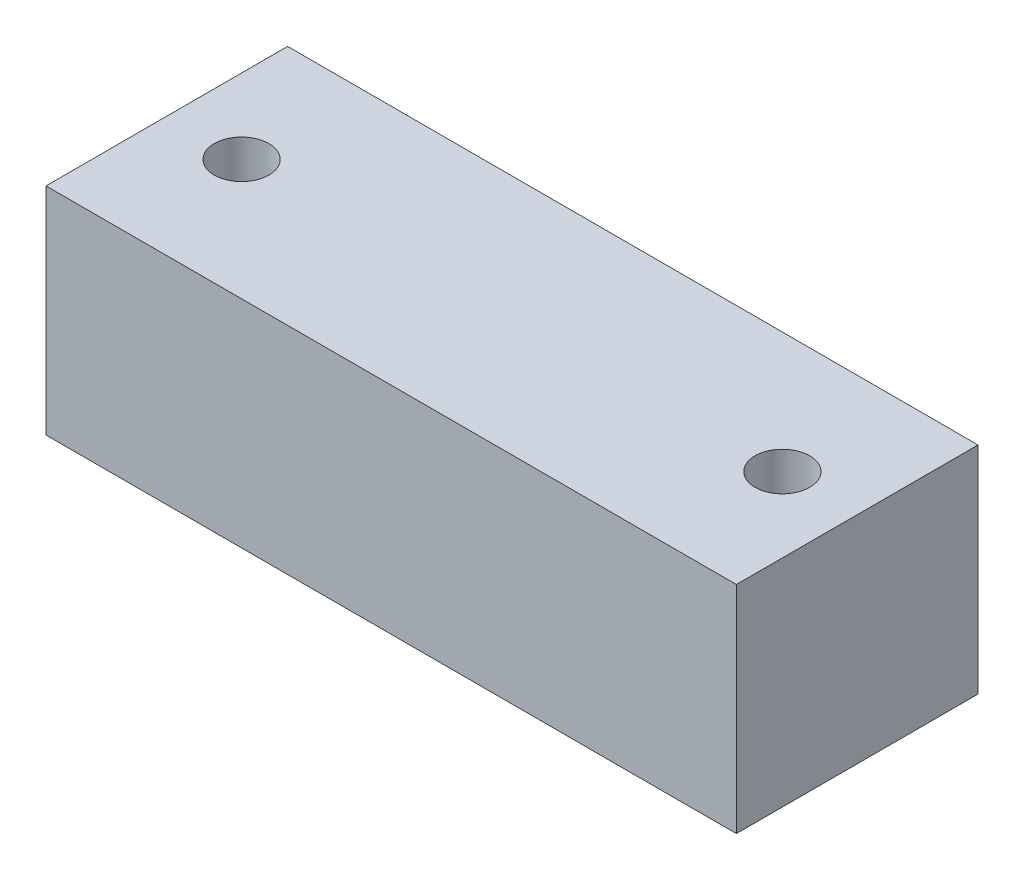
SolidWorks part; units mm, degrees
ref_plane "Alzado" through (0, 0, 0) normal (0, 0, 1) x (1, 0, 0)
ref_plane "Planta" through (0, 0, 0) normal (0, 1, 0) x (1, 0, 0)
ref_plane "Vista lateral" through (0, 0, 0) normal (1, 0, 0) x (0, 0, -1)
sketch "Croquis1" plane through (0, 0, 0) normal (0, 1, 0) x (1, 0, 0)
  line L1 (24, -8.4) -> (-24, -8.4)
  line L2 (24, -8.4) -> (24, 8.4)
  line L3 (24, 8.4) -> (-24, 8.4)
  line L4 (-24, -8.4) -> (-24, 8.4)
  line L5 (24, -8.4) -> (-24, 8.4) construction
  line L6 (24, 8.4) -> (-24, -8.4) construction
  circle A0 centre (-18.8, 0) radius 1.9
  circle A1 centre (18.8, 0) radius 1.9
  point P0 (0, 0)
  dimension "D3" = 3.8
  dimension "D1" = 16.8
  dimension "D2" = 48
  dimension "D4" = 5.2
  dimension "D5" = 5.2
extrude "Saliente-Extruir1" add sketch "Croquis1" along normal blind 15
